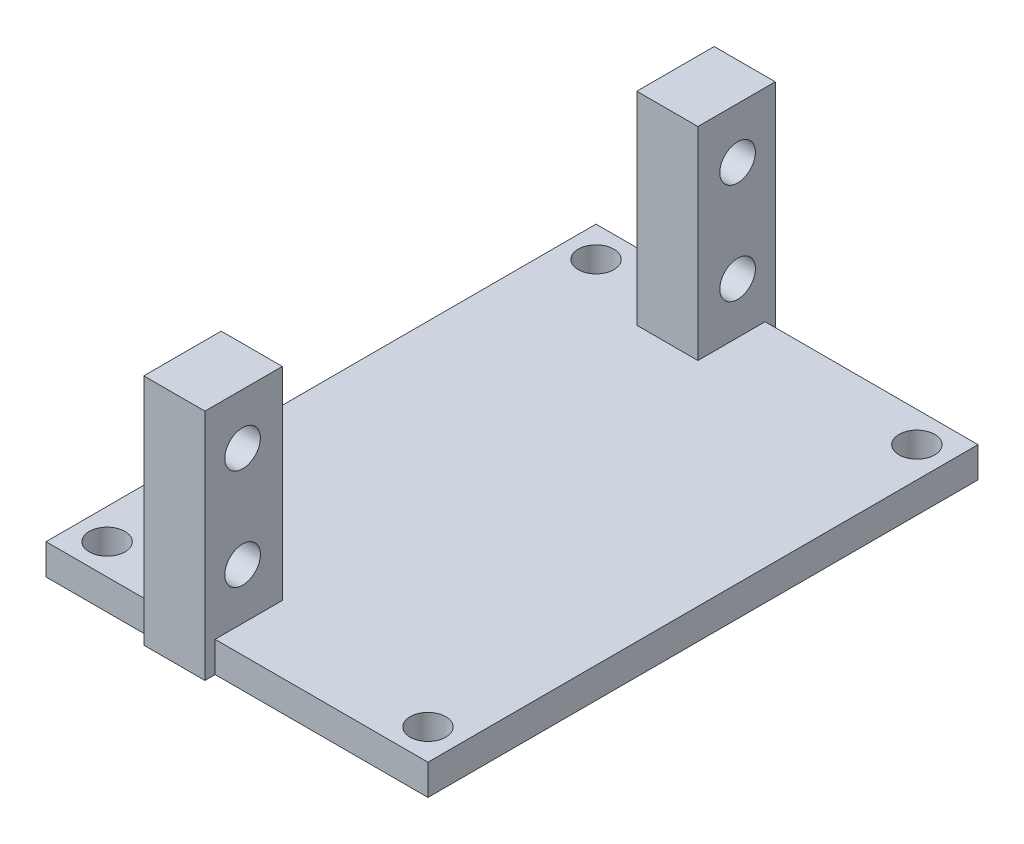
SolidWorks part; units mm, degrees
ref_plane "前视基准面" through (0, 0, 0) normal (0, 0, 1) x (1, 0, 0)
ref_plane "上视基准面" through (0, 0, 0) normal (0, 1, 0) x (1, 0, 0)
ref_plane "右视基准面" through (0, 0, 0) normal (1, 0, 0) x (0, 0, -1)
sketch "草图1" plane through (0, 0, 0) normal (0, 1, 0) x (1, 0, 0)
  line L1 (-18.75, 27) -> (18.75, 27)
  line L2 (-18.75, 27) -> (-18.75, -27)
  line L3 (-18.75, -27) -> (18.75, -27)
  line L4 (18.75, 27) -> (18.75, -27)
  line L5 (-18.75, 27) -> (18.75, -27) construction
  line L6 (-18.75, -27) -> (18.75, 27) construction
  point P0 (0, 0)
  dimension "D1" = 37.5
  dimension "D2" = 54
extrude "凸台-拉伸1" add sketch "草图1" along normal blind 3
sketch "草图2" plane through (0, 3, 0) normal (0, 1, 0) x (1, 0, 0)
  line L1 (-2.15, -28) -> (-8.15, -28)
  line L2 (-2.15, -28) -> (-2.15, -20.4)
  line L3 (-2.15, -20.4) -> (-8.15, -20.4)
  line L4 (-8.15, -28) -> (-8.15, -20.4)
  line L5 (-18.75, 0) -> (18.75, 0) construction
  line L6 (18.75, -27) -> (18.75, 27) construction
  line L8 (-2.15, 28) -> (-8.15, 28)
  line L9 (-2.15, 28) -> (-2.15, 20.4)
  line L10 (-2.15, 20.4) -> (-8.15, 20.4)
  line L11 (-8.15, 28) -> (-8.15, 20.4)
  line L12 (-18.75, 27) -> (-18.75, -27) construction
  point P4 (0, 0)
  dimension "D1" = 26.9
  dimension "D2" = 6
  dimension "D3" = 40.8
extrude "凸台-拉伸2" add sketch "草图2" along normal blind 19.9 and the other way blind 3
sketch "草图3" plane through (-2.15, 0, 0) normal (1, 0, 0) x (0, 0, -1)
  line L0 (-20.4, 12.95) -> (20.4, 12.95) construction
  line L1 (-20.4, 22.9) -> (-20.4, 3) construction
  line L2 (20.4, 22.9) -> (20.4, 3) construction
  line L4 (-24.3, 17.9) -> (24.3, 17.9) construction
  line L5 (-24.3, 17.9) -> (-24.3, 8) construction
  line L6 (-24.3, 8) -> (24.3, 8) construction
  line L7 (24.3, 17.9) -> (24.3, 8) construction
  line L8 (-24.3, 17.9) -> (24.3, 8) construction
  line L9 (-24.3, 8) -> (24.3, 17.9) construction
  circle A0 centre (-24.3, 17.9) radius 1.75
  circle A1 centre (-24.3, 8) radius 1.75
  circle A2 centre (24.3, 8) radius 1.75
  circle A3 centre (24.3, 17.9) radius 1.75
  point P6 (0, 12.95)
  dimension "D3" = 3.5
  dimension "D4" = 3.5
  dimension "D5" = 3.5
  dimension "D6" = 3.5
  dimension "D1" = 9.9
  dimension "D2" = 48.6
extrude "切除-拉伸1" cut sketch "草图3" against normal through all
sketch3d "中心" plane through (0, 0, 0) normal (0, 0, 1) x (1, 0, 0)
  dimension "D1" = 28.7
sketch "草图4" plane through (0, 3, 0) normal (0, 1, 0) x (1, 0, 0)
  line L0 (18.75, 27) -> (-2.15, 27) construction
  line L1 (-15.75, 24) -> (15.75, 24) construction
  line L2 (-15.75, 24) -> (-15.75, -24) construction
  line L3 (-15.75, -24) -> (15.75, -24) construction
  line L4 (15.75, 24) -> (15.75, -24) construction
  line L5 (-18.75, -27) -> (-8.15, -27) construction
  line L6 (-18.75, 27) -> (-18.75, -27) construction
  line L7 (18.75, -27) -> (18.75, 27) construction
  circle A0 centre (-15.75, 24) radius 1.75
  circle A1 centre (-15.75, -24) radius 1.75
  circle A2 centre (15.75, -24) radius 1.75
  circle A3 centre (15.75, 24) radius 1.75
  dimension "D1" = 3.5
  dimension "D2" = 3.5
  dimension "D3" = 3.5
  dimension "D4" = 3.5
  dimension "D5" = 3
  dimension "D6" = 3
  dimension "D7" = 3
  dimension "D8" = 3
extrude "切除-拉伸2" cut sketch "草图4" against normal through all
